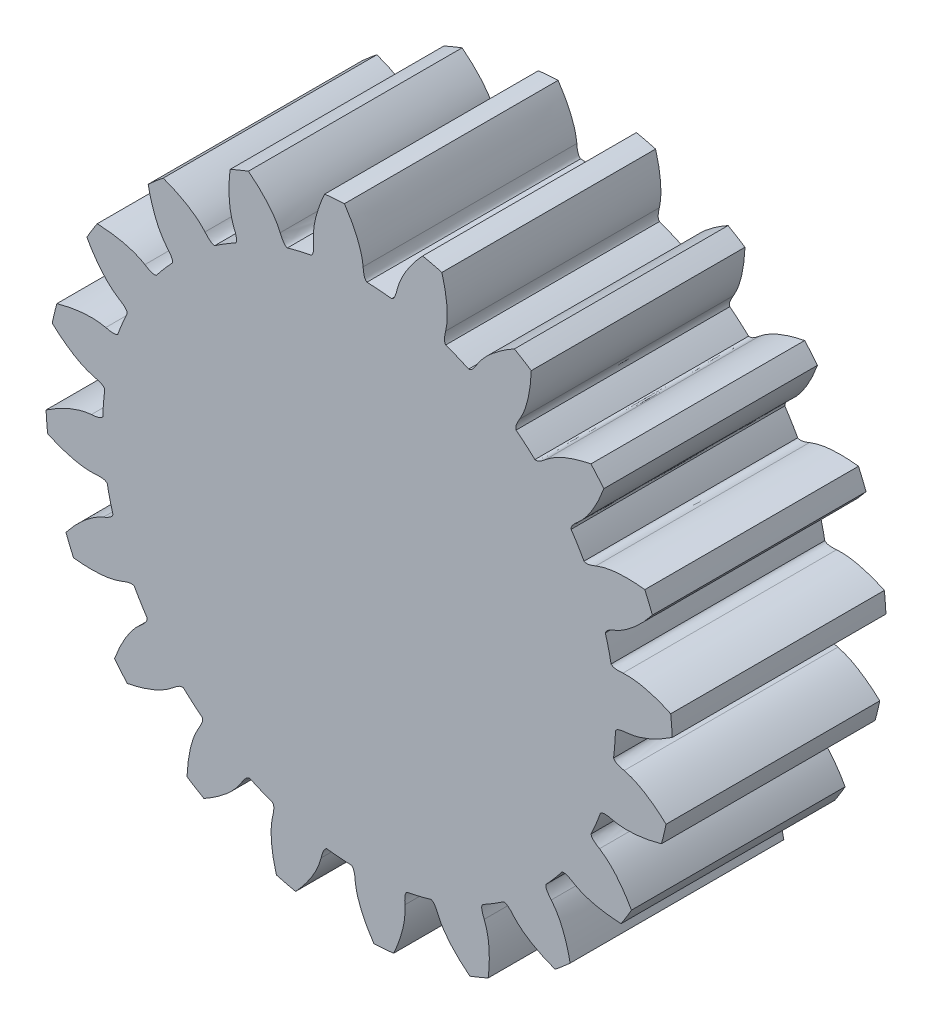
SolidWorks part; units mm, degrees
ref_plane "Front Plane" through (0, 0, 0) normal (0, 0, 1) x (1, 0, 0)
ref_plane "Top Plane" through (0, 0, 0) normal (0, 1, 0) x (1, 0, 0)
ref_plane "Right Plane" through (0, 0, 0) normal (1, 0, 0) x (0, 0, -1)
sketch "involute" plane through (0, 0, 0) normal (0, 0, 1) x (1, 0, 0)
  line L0 (0, 0) -> (0, 12.7) construction
  line L1 (0, 0) -> (-4.0817, 11.2144) construction
  line L2 (-4.0817, 11.2144) -> (0, 12.7) construction
  line L3 (-6.6755, 9.8925) -> (-0.6557, 13.9546) construction
  line L4 (-5.977, 10.3295) -> (-0.4046, 13.5539) construction
  line L5 (-5.14, 10.7705) -> (-0.1837, 13.1357) construction
  line L6 (0, 12.7) -> (-0.1837, 13.1357) construction
  line L7 (-0.1837, 13.1357) -> (-0.4046, 13.5539) construction
  line L8 (-0.4046, 13.5539) -> (-0.6557, 13.9546) construction
  circle A0 centre (0, 0) radius 12.7 construction
  arc A1 (-6.6755, 9.8925) -> (-4.0817, 11.2144) centre (0, 0) cw construction
  circle A2 centre (0, 0) radius 13.97 construction
  arc A3 (-4.0817, 11.2144) -> (0.1779, 11.9328) centre (0, 0) cw construction
  arc A4 (0.1779, 11.9328) -> (-5.977, 10.3295) centre (0, 0) ccw construction
  arc A5 (0.1779, 11.9328) -> (-5.14, 10.7705) centre (0, 0) ccw construction
  dimension "D1" = 25.4
  dimension "D4" = 27.94
  dimension "D2" = 20
  dimension "D3" = 4.3437
  dimension "D5" = 7.2621
  dimension "D6" = 4.3437
  dimension "D7" = 2.9185
sketch "undercut" plane through (0, 0, 0) normal (0, 0, 1) x (1, 0, 0)
  line L0 (0.1779, 11.9328) -> (0.3455, 11.4248) construction
  line L1 (-7.683, 11.6676) -> (8.3741, 11.1819) construction
  line L2 (0.1779, 11.9328) -> (0.1892, 11.7957) construction
  line L3 (-4.7423, 13.1405) -> (10.7562, 8.9143) construction
  line L4 (-6.1616, 12.5378) -> (9.7083, 10.0454) construction
  line L5 (0.2567, 11.5298) -> (0.1779, 11.9328) construction
  line L6 (0.3455, 11.4248) -> (0.2567, 11.5298) construction
  line L7 (10.3167, 9.4195) -> (-5.3665, 12.8981) construction
  line L8 (0.2137, 11.6604) -> (0.1779, 11.9328) construction
  line L9 (0.2137, 11.6604) -> (0.2567, 11.5298) construction
  line L10 (0.1892, 11.7957) -> (0.2137, 11.6604) construction
  circle A0 centre (0, 0) radius 13.97 construction
  dimension "D1" = 70
  dimension "D2" = 11.43
  dimension "D3" = 70
  dimension "D4" = 11.43
  dimension "D5" = 70
  dimension "D6" = 11.43
  dimension "D7" = 70
  dimension "D8" = 11.43
sketch "Sketch2" plane through (0, 0, 0) normal (0, 0, 1) x (1, 0, 0)
  circle A0 centre (0, 0) radius 13.97
extrude "Boss-Extrude1" add sketch "Sketch2" along normal mid plane 9.525
sketch "Sketch3" plane through (0, 0, 4.7625) normal (0, 0, 1) x (1, 0, 0)
  line L0 (0, 12.7) -> (0, 0) construction
  line L1 (0, 0) -> (0.8968, 11.3948) construction
  arc A0 (0.3455, 11.4248) -> (1.4459, 11.3382) centre (0, 0) cw
  arc A1 (-0.6557, 13.9546) -> (2.8306, 13.6802) centre (0, 0) cw
  spline S0 degree 3 poles (-0.6557, 13.9546) (-0.4792, 13.6933) (-0.1076, 13.0565) (0.138, 12.3566) (0.1779, 11.9328) knots 0 0 0 0 0.428684 1 1 1 1
  spline S1 degree 3 poles (0.1779, 11.9328) (0.1811, 11.8405) (0.2049, 11.6602) (0.2639, 11.4806) (0.3455, 11.4248) knots 0 0 0 0 0.5 1 1 1 1
  spline S2 degree 3 poles (2.8306, 13.6802) (2.6154, 13.4497) (2.1487, 12.879) (1.7967, 12.2261) (1.691, 11.8137) knots 0 0 0 0 0.428684 1 1 1 1
  spline S3 degree 3 poles (1.691, 11.8137) (1.6734, 11.7231) (1.6217, 11.5487) (1.5354, 11.3805) (1.4459, 11.3382) knots 0 0 0 0 0.5 1 1 1 1
  point P32 (2.7602, 13.6802)
  dimension "D1" = 4.5
extrude "Cut-Extrude1" cut sketch "Sketch3" against normal through all both and the other way through all
pattern_circular "CirPattern1" count 20 over 360 about axis through (0, 0, 4.7625) along (0, 0, -1) of "Cut-Extrude1"
equation "\"n\" = 20"
equation "\"dp\" = 20"
equation "\"a\"= 20"
equation "\"m\" = 1 / \"dp\""
equation "\"pd\"= \"n\" / \"dp\""
equation "\"add\"= \"m\""
equation "\"ded\"= 1.25 * \"m\""
equation "\"od\"= \"pd\" + 2 * \"add\""
equation "\"rd\"= \"pd\" - 2 * \"add\""
equation "\"D1@involute\" = \"pd\""
equation "\"D2@involute\" = \"a\""
equation "\"D4@involute\" = \"od\""
equation "\"D6@involute\" = \"D3@involute\""
equation "\"D7@involute\" = \"D5@involute\" - \"D3@involute\""
equation "\"D1@undercut\" = 90 - \"a\""
equation "\"D2@undercut\" = \"rd\" / 2"
equation "\"D3@undercut\" = 90 - \"a\""
equation "\"D4@undercut\" = \"D2@undercut\""
equation "\"D5@undercut\" = \"D3@undercut\""
equation "\"D6@undercut\" = \"D2@undercut\""
equation "\"D7@undercut\" = \"D3@undercut\""
equation "\"D8@undercut\" = \"D2@undercut\""
equation "\"D1@Sketch3\"=90/\"n\""
equation "\"D1@CirPattern1\"=\"n\""
